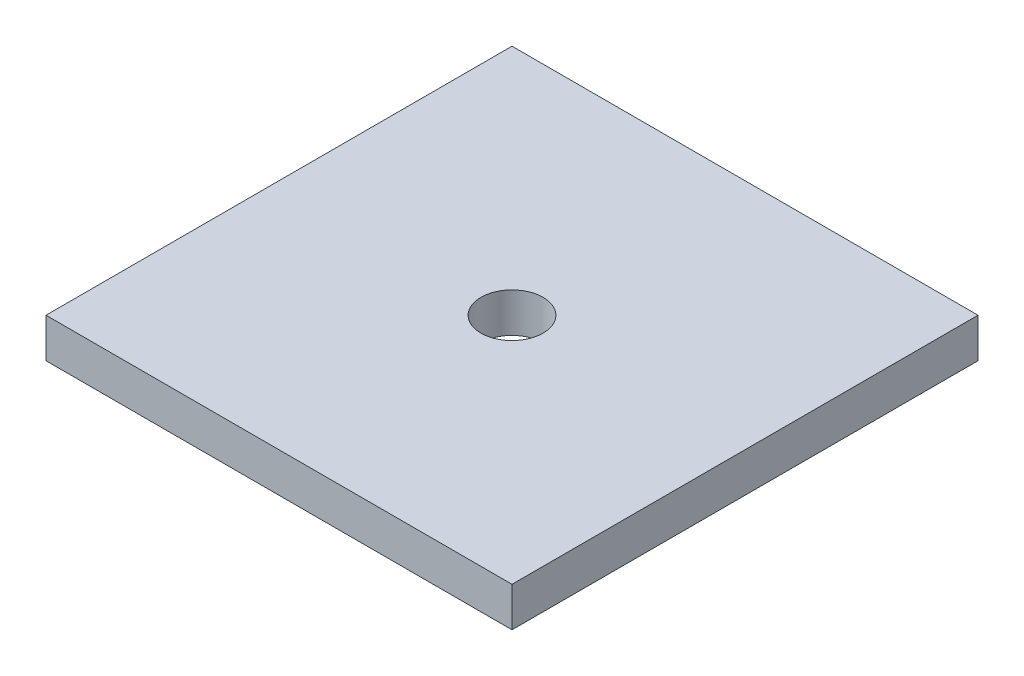
SolidWorks part; units mm, degrees
material "Pine"
ref_plane "Front Plane" through (0, 0, 0) normal (0, 0, 1) x (1, 0, 0)
ref_plane "Top Plane" through (0, 0, 0) normal (0, 1, 0) x (1, 0, 0)
ref_plane "Right Plane" through (0, 0, 0) normal (1, 0, 0) x (0, 0, -1)
sketch "Sketch1" plane through (0, 0, 0) normal (0, 1, 0) x (1, 0, 0)
  line L0 (-37.5, 37.5) -> (37.5, -37.5) construction
  line L1 (-37.5, 37.5) -> (37.5, 37.5)
  line L2 (-37.5, 37.5) -> (-37.5, -37.5)
  line L3 (-37.5, -37.5) -> (37.5, -37.5)
  line L4 (37.5, 37.5) -> (37.5, -37.5)
  dimension "D1" = 75
extrude "Extrude1" add sketch "Sketch1" along normal blind 6.35
hole_wizard "Ø10.0 (10) Diameter Hole1" positions "Sketch3" profile "Sketch4" hole size "Ø10.0" standard "Ansi Metric" end condition through all
sketch "Sketch3" plane through (0, 6.35, 0) normal (0, 1, 0) x (-1, 0, 0)
  point P0 (0, 0)
sketch "Sketch4" plane through (0, 6.35, 0) normal (1, 0, 0) x (0, 0, 1)
  line L0 (0, 0) -> (0, 6.35)
  line L1 (0, 6.35) -> (5, 6.35)
  line L2 (5, 6.35) -> (5, 0)
  line L5 (5, 0) -> (0, 0)
  line L11 (0, -6.35) -> (0, 107.95) construction
  dimension "Thru Hole Dia." = 10
  dimension "Thru Hole Depth" = 6.35
